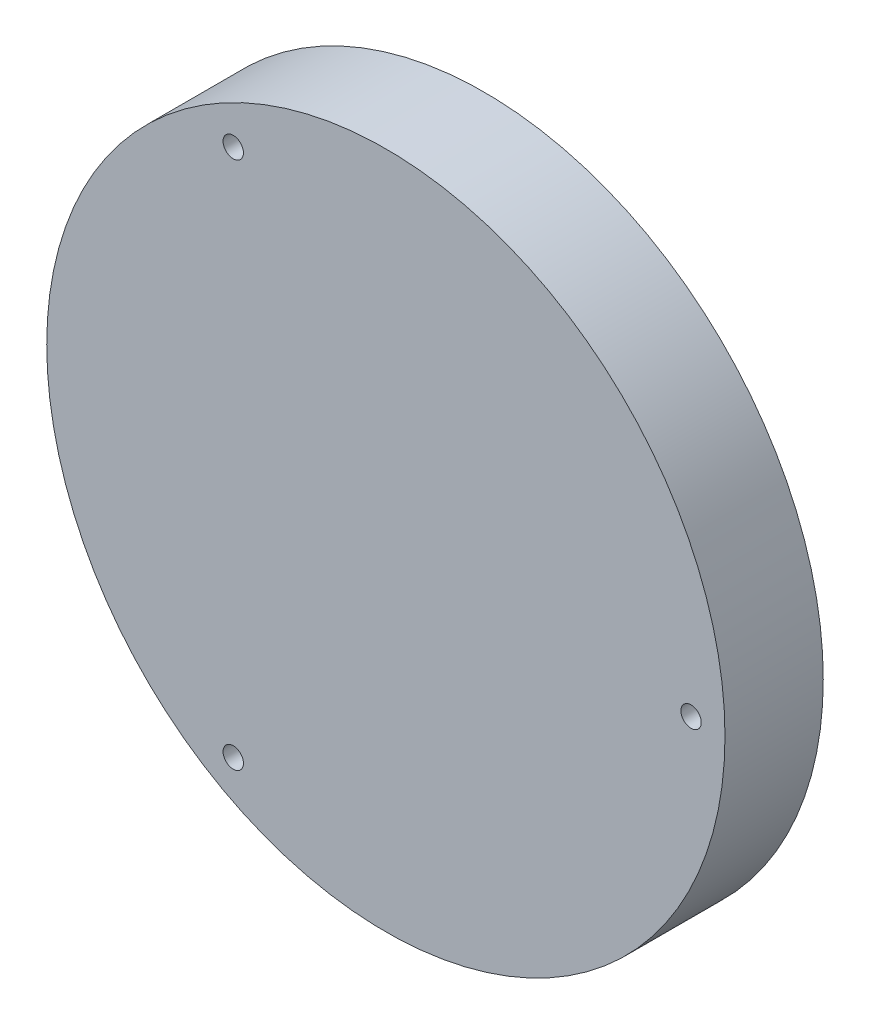
SolidWorks part; units mm, degrees
ref_plane "Front Plane" through (0, 0, 0) normal (1, 0, 0) x (0, 1, 0)
ref_plane "Top Plane" through (0, 0, 0) normal (0, 0, 1) x (0, 1, 0)
ref_plane "Right Plane" through (0, 0, 0) normal (0, 1, 0) x (-1, 0, 0)
sketch "Sketch2" plane through (0, 0, 0) normal (0, 0, 1) x (0, 1, 0)
  line L4 (0, -45) -> (38.9711, 22.5)
  line L5 (38.9711, 22.5) -> (-38.9711, 22.5)
  line L6 (-38.9711, 22.5) -> (0, -45)
  circle A2 centre (0, 0) radius 50
  circle A4 centre (0, 0) radius 22.5 construction
  circle A5 centre (-38.9711, 22.5) radius 1.5
  circle A6 centre (38.9711, 22.5) radius 1.5
  circle A7 centre (0, -45) radius 1.5
  dimension "D1" = 100
  dimension "D2" = 3
  dimension "D3" = 3
  dimension "D4" = 3
  dimension "D5" = 45
extrude "Boss-Extrude1" add sketch "Sketch2" along normal blind 14.4886 contours A2 A7 L6 A5 L5 A6 L4 | A7 L4 A6 L5 A5 L6
